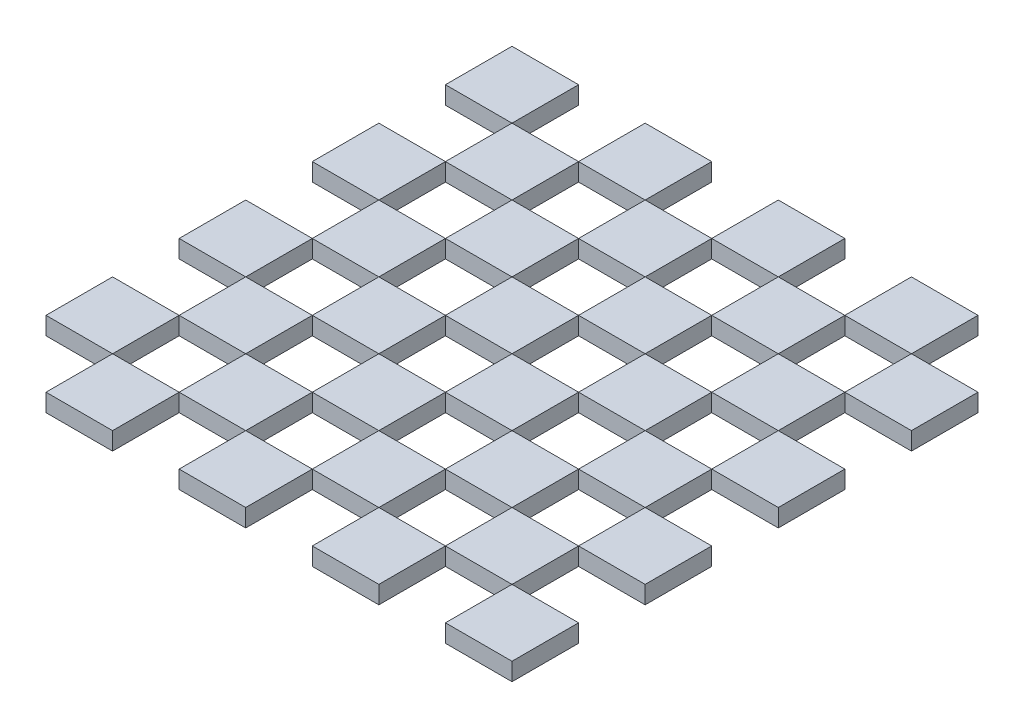
SolidWorks part; units mm, degrees
material "AISI 304"
ref_plane "Front Plane" through (0, 0, 0) normal (0, 0, 1) x (1, 0, 0)
ref_plane "Top Plane" through (0, 0, 0) normal (0, 1, 0) x (1, 0, 0)
ref_plane "Right Plane" through (0, 0, 0) normal (1, 0, 0) x (0, 0, -1)
sketch "Sketch1" plane through (0, 0, 0) normal (0, 1, 0) x (1, 0, 0)
  line L0 (0, 150) -> (0, -150)
  line L1 (-150, -150) -> (150, -150)
  line L2 (-150, -150) -> (-150, 150)
  line L3 (-150, 150) -> (150, 150)
  line L4 (150, -150) -> (150, 150)
  line L5 (-150, -150) -> (150, 150) construction
  line L6 (-150, 150) -> (150, -150) construction
  line L7 (-112.5, 150) -> (-112.5, -150)
  line L8 (37.5, 150) -> (37.5, -150)
  line L9 (-75, 150) -> (-75, -150)
  line L10 (-37.5, 150) -> (-37.5, -150)
  line L11 (75, 150) -> (75, -150)
  line L12 (112.5, 150) -> (112.5, -150)
  line L13 (-150, -75) -> (150, -75)
  line L14 (-150, 37.5) -> (150, 37.5)
  line L15 (-150, 75) -> (150, 75)
  line L16 (-150, -112.5) -> (150, -112.5)
  line L17 (-150, 0) -> (150, 0)
  line L18 (-150, -37.5) -> (150, -37.5)
  line L19 (-150, 112.5) -> (150, 112.5)
  point P0 (0, 0)
  point P20 (0, 0)
  point P35 (-150, 116.087)
  point P36 (-150, 89.5251)
  point P37 (150, 89.5251)
  point P38 (150, 57.7454)
  point P39 (150, 24.5505)
  point P40 (0, 0)
  point P41 (-150, 31.9565)
  point P42 (-150, -29.3478)
  point P43 (150, -34.5652)
  point P44 (-150, -67.1739)
  point P45 (150, -69.7826)
  point P46 (150, -103.0435)
  point P47 (-150, -111.5217)
  dimension "D1" = 300
  dimension "D2" = 37.5
  dimension "D3" = 37.5
  dimension "D4" = 37.5
  dimension "D5" = 37.5
  dimension "D6" = 37.5
  dimension "D7" = 37.5
  dimension "D8" = 37.5
  dimension "D9" = 37.5
  dimension "D10" = 37.5
  dimension "D11" = 37.5
  dimension "D12" = 37.5
  dimension "D13" = 37.5
extrude "Boss-Extrude1" add sketch "Sketch1" along normal blind 10 contours L2 L19 L7 L3 | L19 L7 L15 L9 | L15 L2 L14 L7 | L2 L18 L7 L17 | L2 L16 L7 L13 | L16 L7 L1 L9 | L18 L7 L13 L9 | L7 L17 L9 L14 | L9 L19 L10 L3 | L15 L9 L14 L10 | L9 L18 L10 L17 | L9 L16 L10 L13 | L16 L10 L1 L0 | L18 L10 L13 L0 | L10 L17 L0 L14 | L19 L10 L15 L0 | L0 L19 L8 L3 | L15 L0 L14 L8 | L0 L18 L8 L17 | L0 L16 L8 L13 | L16 L8 L1 L11 | L18 L8 L13 L11 | L8 L17 L11 L14 | L19 L8 L15 L11 | L11 L19 L12 L3 | L15 L11 L14 L12 | L11 L18 L12 L17 | L11 L16 L12 L13 | L16 L12 L1 L4 | L18 L12 L13 L4 | L12 L17 L4 L14 | L19 L12 L15 L4
